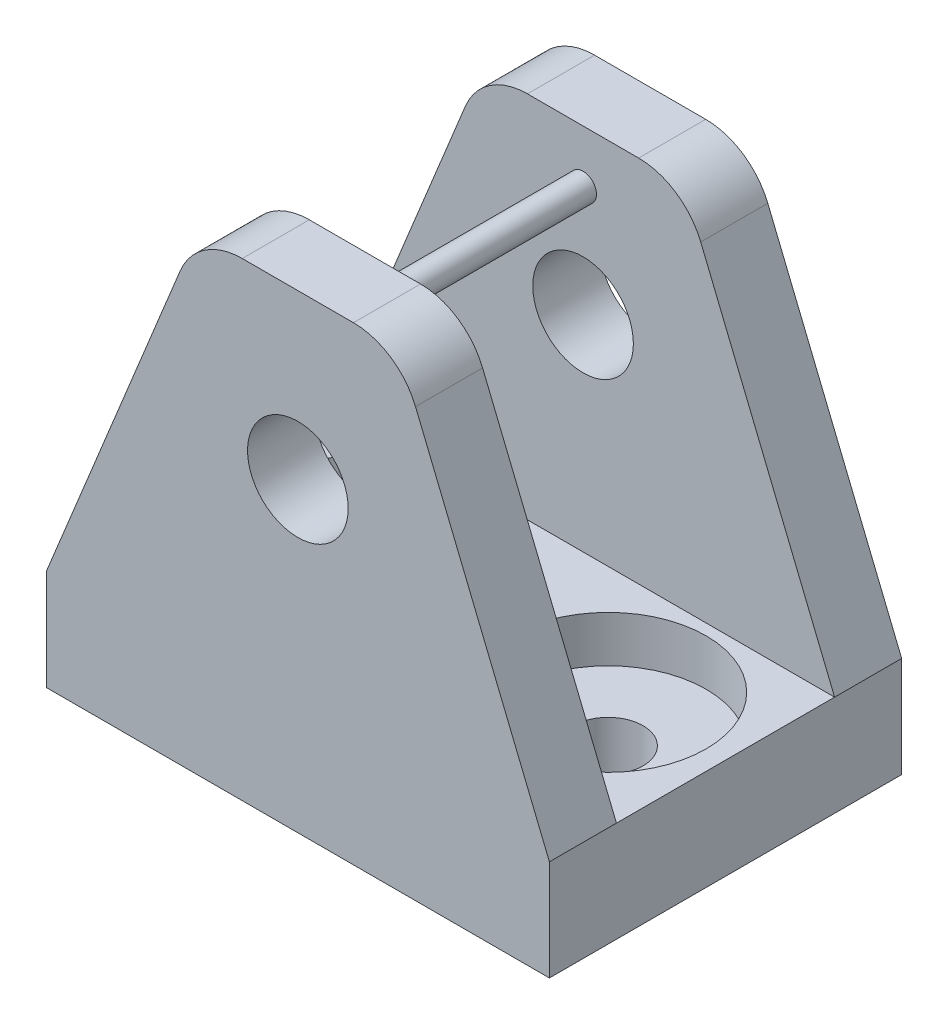
SolidWorks part; units mm, degrees
material "6061-T6 (SS)"
ref_plane "X-Y Datum" through (0, 0, 0) normal (0, 0, 1) x (1, 0, 0)
ref_plane "X-Z Datum" through (0, 0, 0) normal (0, 1, 0) x (1, 0, 0)
ref_plane "Y-Z Datum" through (0, 0, 0) normal (1, 0, 0) x (0, 0, -1)
sketch "Sketch1" plane through (0, 0, 0) normal (0, 1, 0) x (1, 0, 0)
  line L1 (-23.8125, -16.6751) -> (23.8125, -16.6751)
  line L2 (-23.8125, -16.6751) -> (-23.8125, 16.6751)
  line L3 (-23.8125, 16.6751) -> (23.8125, 16.6751)
  line L4 (23.8125, -16.6751) -> (23.8125, 16.6751)
  line L5 (-23.8125, -16.6751) -> (23.8125, 16.6751) construction
  line L6 (-23.8125, 16.6751) -> (23.8125, -16.6751) construction
  point P0 (0, 0)
  dimension "D1" = 47.625
  dimension "D2" = 33.3502
extrude "Boss-Extrude1" add sketch "Sketch1" along normal blind 44.45
sketch "Sketch2" plane through (0, 44.45, 0) normal (0, 1, 0) x (1, 0, 0)
  line L0 (23.8125, -16.6751) -> (23.8125, 16.6751) construction
  line L1 (-23.8125, -10.3251) -> (23.8125, -10.3251)
  line L2 (-23.8125, -10.3251) -> (-23.8125, 10.3251)
  line L3 (-23.8125, 10.3251) -> (23.8125, 10.3251)
  line L4 (23.8125, -10.3251) -> (23.8125, 10.3251)
  line L5 (-23.8125, -10.3251) -> (23.8125, 10.3251) construction
  line L6 (-23.8125, 10.3251) -> (23.8125, -10.3251) construction
  line L7 (23.8125, 16.6751) -> (-23.8125, 16.6751) construction
  point P0 (0, 0)
  dimension "D1" = 6.35
extrude "Cut-Extrude1" cut sketch "Sketch2" against normal offset from surface (34.925 mm away) 9.525 up to face at (0, 0, 0)
sketch "Sketch3" plane through (0, 0, -16.6751) normal (0, 0, -1) x (-1, 0, 0)
  line L9 (9.525, 44.45) -> (23.8125, 44.45)
  line L10 (-23.8125, 44.45) -> (23.8125, 44.45) construction
  line L11 (23.8125, 44.45) -> (23.8125, 9.525)
  line L12 (23.8125, 44.45) -> (23.8125, 0) construction
  line L13 (23.8125, 9.525) -> (9.525, 44.45)
  line L14 (-23.8125, 0) -> (23.8125, 0) construction
  line L15 (0, 0) -> (0, -50000) construction
  line L17 (-23.8125, 44.45) -> (-23.8125, 9.525)
  line L18 (-9.525, 44.45) -> (-23.8125, 44.45)
  line L19 (-23.8125, 9.525) -> (-9.525, 44.45)
  line M2 (23.8125, 0) -> (23.8125, 44.45)
  line M3 (23.8125, 44.45) -> (-23.8125, 44.45)
  line M4 (-23.8125, 44.45) -> (-23.8125, 0)
  dimension "D1" = 9.525
  dimension "D2" = 19.05
extrude "Cut-Extrude2" cut sketch "Sketch3" against normal through all and the other way through all contours L13 M2 M3 | L19 M4 M3
hole_wizard "CBORE for M6 Hex Head Bolt1" positions "Sketch6" profile "Sketch7" counterbore size "M6" standard "ANSI Metric"
sketch "Sketch6" plane through (0, 9.525, 0) normal (0, 1, 0) x (1, 0, 0)
  line L0 (0, 0) -> (0, 50000) construction
  line L1 (0, 0) -> (50000, 0) construction
  point P0 (-12.7, 0)
  point P2 (12.7, 0)
  dimension "D1" = 12.7
  dimension "D2" = 12.7
sketch "Sketch7" plane through (-12.7, 9.525, 0) normal (1, 0, 0) x (0, 0, 1)
  line L0 (0, 0) -> (0, 16.002)
  line L1 (0, 16.002) -> (3.3, 14.0192)
  line L2 (3.3, 14.0192) -> (3.3, 4.38)
  line L3 (3.3, 4.38) -> (9.275, 4.38)
  line L4 (9.275, 4.38) -> (9.275, 0)
  line L5 (9.275, 0) -> (0, 0)
  line L10 (0, 16.002) -> (-3.3, 14.0192) construction
  line L11 (0, -6.35) -> (0, 107.95) construction
  dimension "Hole Dia." = 6.6
  dimension "Hole Depth" = 16.002
  dimension "C'Bore Dia." = 18.55
  dimension "C'Bore Depth" = 4.38
  dimension "Drill Angle" = 118
sketch "Sketch8" plane through (0, 9.525, 0) normal (0, 1, 0) x (1, 0, 0)
  line L0 (-3.175, 0) -> (3.175, 0) construction
  line L1 (-3.175, 6.35) -> (3.175, 6.35)
  line L2 (-3.175, -6.35) -> (3.175, -6.35)
  arc A0 (-3.175, 6.35) -> (-3.175, -6.35) centre (-3.175, 0) ccw
  arc A1 (3.175, -6.35) -> (3.175, 6.35) centre (3.175, 0) ccw
  point P3 (0, 0)
  dimension "D2" = 6.35
  dimension "D1" = 6.35
fillet "Fillet3" radius 6.35 4 edges at (9.525, 44.45, 13.5001) (-9.525, 44.45, 13.5001) (9.525, 44.45, -13.5001) (-9.525, 44.45, -13.5001)
extrude "Cut-Extrude3" [suppressed] cut sketch "Sketch8" against normal through all
hole_wizard "3/8 (0.375) Diameter Hole1" positions "Sketch9" profile "Sketch11" hole size "3/8" standard "ANSI Inch" end condition through all
sketch "Sketch9" plane through (0, 0, 16.6751) normal (0, 0, 1) x (1, 0, 0)
  line L0 (-23.8125, 0) -> (23.8125, 0) construction
  point P0 (0, 28.9695)
  dimension "D1" = 28.9695
sketch "Sketch11" plane through (0, 28.9695, 16.6751) normal (1, 0, 0) x (0, -1, 0)
  line L0 (0, 0) -> (0, 33.3503)
  line L1 (0, 33.3503) -> (4.7625, 33.3503)
  line L2 (4.7625, 33.3503) -> (4.7625, 0)
  line L5 (4.7625, 0) -> (0, 0)
  line L11 (0, -6.35) -> (0, 107.95) construction
  dimension "Thru Hole Dia." = 9.525
  dimension "Thru Hole Depth" = 33.3503
sketch3d "3DSketch1"
  line L0 (18.4533, 9.525, 7.275) -> (-6.9467, 9.525, 7.275)
  line L1 (12.7181, 9.525, -9.275) -> (-12.7181, 9.525, -9.275)
  circle A0 centre (12.7, 9.525, 0) radius 9.275 construction
  circle A1 centre (-12.7, 9.525, 0) radius 9.275 construction
  arc A2 (18.4533, 9.525, 7.275) -> (12.7181, 9.525, -9.275) centre (12.7181, 9.525, -0.0063) cw
  arc A3 (-12.7181, 9.525, -9.275) -> (-6.9467, 9.525, 7.275) centre (-6.9467, 9.525, -2.0063) cw
  point P4 (12.7, 18.8, 0)
  point P7 (-12.7, 18.8, 0)
  point P11 (12.7181, 18.7937, -0.0063)
  point P13 (-6.9467, 18.8063, -2.0063)
sketch "Sketch13" plane through (0, 0, -10.3251) normal (0, 0, 1) x (1, 0, 0)
  circle A0 centre (0, 28.9695) radius 10.3124
  circle A1 centre (0, 28.9695) radius 4.7625
  dimension "D1" = 20.6248
sketch "Sketch14" plane through (0, 0, -16.6751) normal (0, 0, -1) x (-1, 0, 0)
  circle A0 centre (0, 28.9695) radius 4.7625
sketch3d "3DSketch2"
  point P0 (-2.8247, 12.9458, -16.6751)
sketch3d "3DSketch3"
  point P0 (5.6212, 14.4993, 16.6751)
sketch "Sketch15" plane through (0, 0, -10.3251) normal (0, 0, 1) x (1, 0, 0)
  circle A0 centre (0, 39.4683) radius 1.27
  dimension "D1" = 2.54
extrude "Boss-Extrude2" add sketch "Sketch15" along normal up to next
